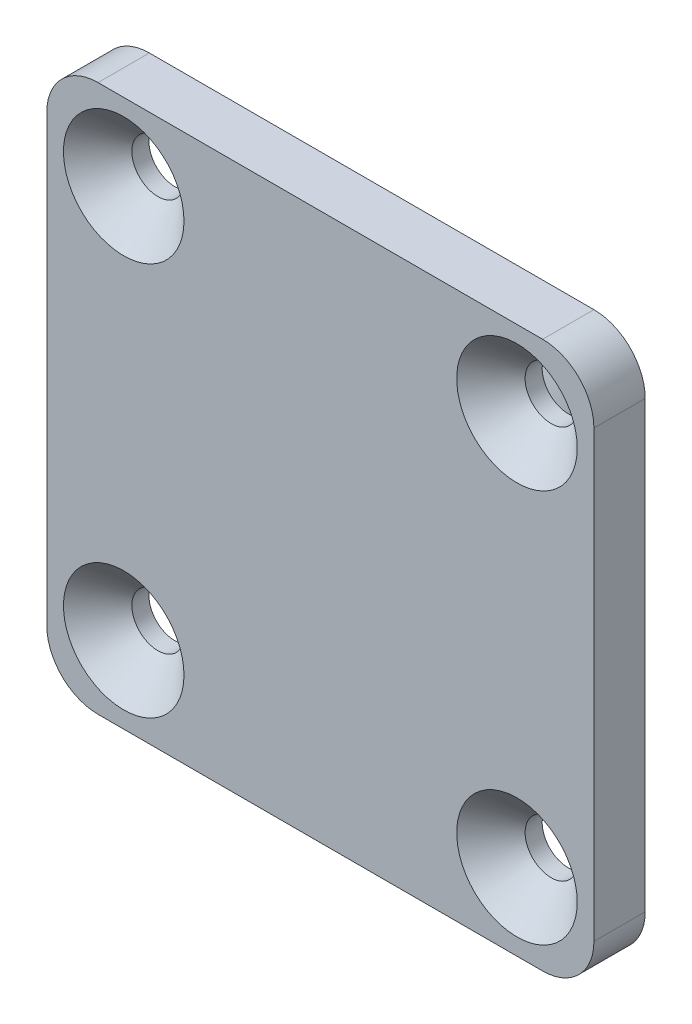
SolidWorks part; units mm, degrees
material "Сталь"
ref_plane "Спереди" through (0, 0, 0) normal (0, 0, 1) x (1, 0, 0)
ref_plane "Сверху" through (0, 0, 0) normal (0, 1, 0) x (1, 0, 0)
ref_plane "Справа" through (0, 0, 0) normal (1, 0, 0) x (0, 0, -1)
sketch "Эскиз1" plane through (0, 0, 0) normal (0, 0, 1) x (1, 0, 0)
  line L4 (13, 16) -> (-13, 16)
  line L5 (-16, 13) -> (-16, -13)
  line L6 (-13, -16) -> (13, -16)
  line L7 (16, -13) -> (16, 13)
  line L8 (13, 16) -> (-13, 16)
  line L9 (-16, 13) -> (-16, -13)
  line L10 (-13, -16) -> (13, -16)
  line L11 (16, -13) -> (16, 13)
  arc A8 (16, 13) -> (13, 16) centre (13, 13) ccw
  arc A9 (16, 13) -> (13, 16) centre (13, 13) ccw
  arc A10 (-13, 16) -> (-16, 13) centre (-13, 13) ccw
  arc A11 (-13, 16) -> (-16, 13) centre (-13, 13) ccw
  arc A12 (-16, -13) -> (-13, -16) centre (-13, -13) ccw
  arc A13 (-16, -13) -> (-13, -16) centre (-13, -13) ccw
  arc A14 (13, -16) -> (16, -13) centre (13, -13) ccw
  arc A15 (13, -16) -> (16, -13) centre (13, -13) ccw
  circle A28 centre (-11.5, -11.5) radius 1.525
  circle A29 centre (-11.5, 11.5) radius 1.525
  circle A30 centre (-11.5, 11.5) radius 1.525
  circle A31 centre (11.5, -11.5) radius 1.525
  circle A32 centre (11.5, 11.5) radius 1.525
  dimension "D1" = 0
  dimension "D2" = 0
extrude "Бобышка-Вытянуть1" add sketch "Эскиз1" along normal blind 3
sketch "Эскиз2" plane through (0, 0, 0) normal (0, 0, -1) x (-1, 0, 0)
  circle A0 centre (0, 0) radius 10
  circle A1 centre (0, 0) radius 7
  dimension "D1" = 20
  dimension "D2" = 3
extrude "Бобышка-Вытянуть2" add sketch "Эскиз2" along normal blind 5.1
chamfer "Фаска1" distance 2 angle 45 4 edges at (-9.975, -11.5, 3) (13.025, -11.5, 3) (13.025, 11.5, 3) (-9.975, 11.5, 3)
